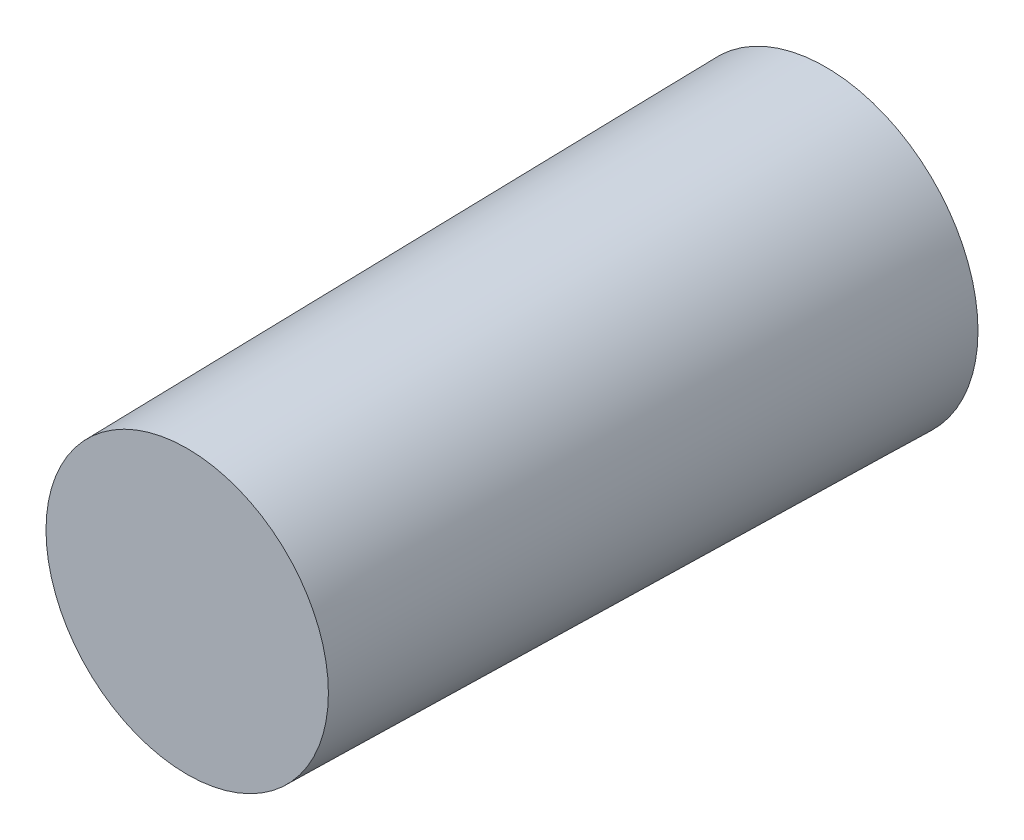
SolidWorks part; units mm, degrees
ref_plane "Front Plane" through (0, 0, 0) normal (0, 0, 1) x (1, 0, 0)
ref_plane "Top Plane" through (0, 0, 0) normal (0, 1, 0) x (1, 0, 0)
ref_plane "Right Plane" through (0, 0, 0) normal (1, 0, 0) x (0, 0, -1)
sketch "Sketch1" plane through (0, 0, 0) normal (0, 0, 1) x (1, 0, 0)
  circle A0 centre (0, 0) radius 2.875
  dimension "D1" = 5.75
extrude "Boss-Extrude1" add sketch "Sketch1" along normal blind 13
draft "Draft1" type of draft neutral plane draft angle 1 faces to draft 1 face at (2.875, 0, 13) neutral plane through (0, 0, 13) neutral plane normal (0, 0, 1) parameters "D1"=1
